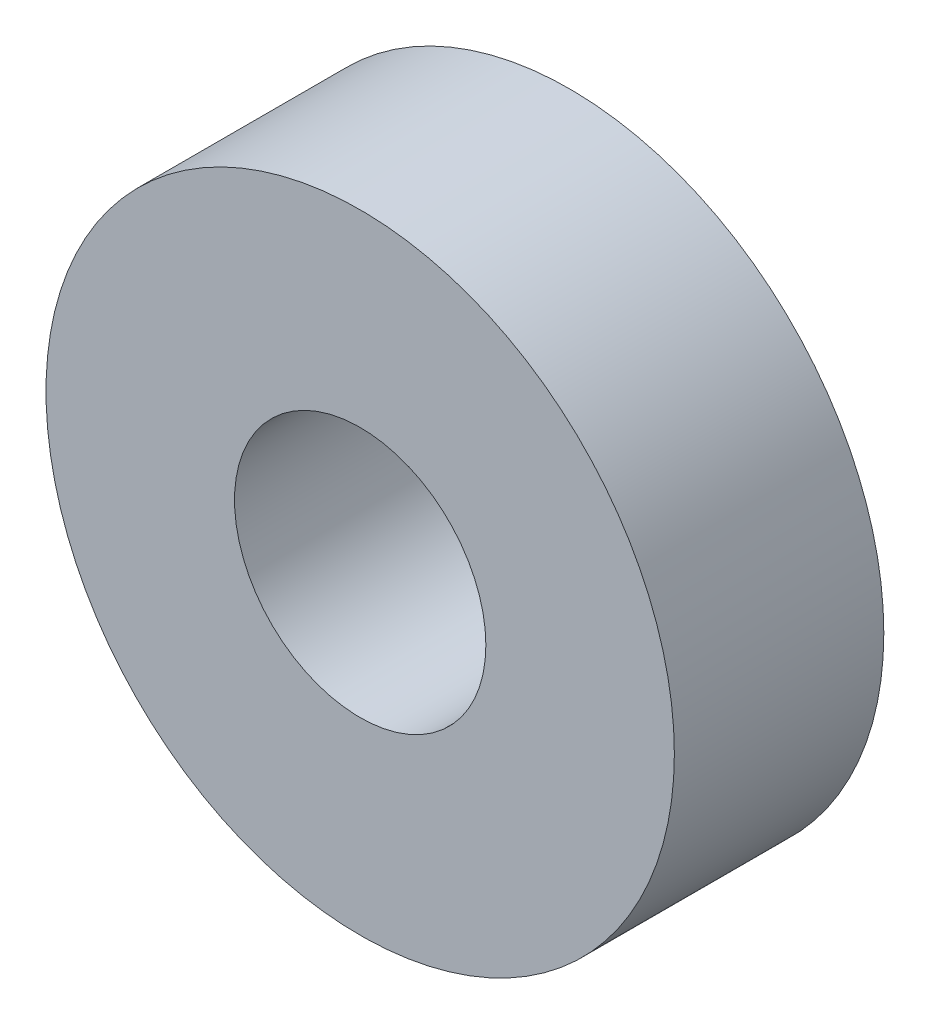
SolidWorks part; units mm, degrees
ref_plane "前视基准面" through (0, 0, 0) normal (0, 0, 1) x (1, 0, 0)
ref_plane "上视基准面" through (0, 0, 0) normal (0, 1, 0) x (1, 0, 0)
ref_plane "右视基准面" through (0, 0, 0) normal (1, 0, 0) x (0, 0, -1)
other "Configuration Table"
sketch "草图1" plane through (0, 0, 0) normal (0, 0, 1) x (1, 0, 0)
  circle A0 centre (0, 0) radius 7.5
  circle A1 centre (0, 0) radius 3
  dimension "D1" = 6
  dimension "D2" = 15
extrude "凸台-拉伸1" add sketch "草图1" along normal blind 5
